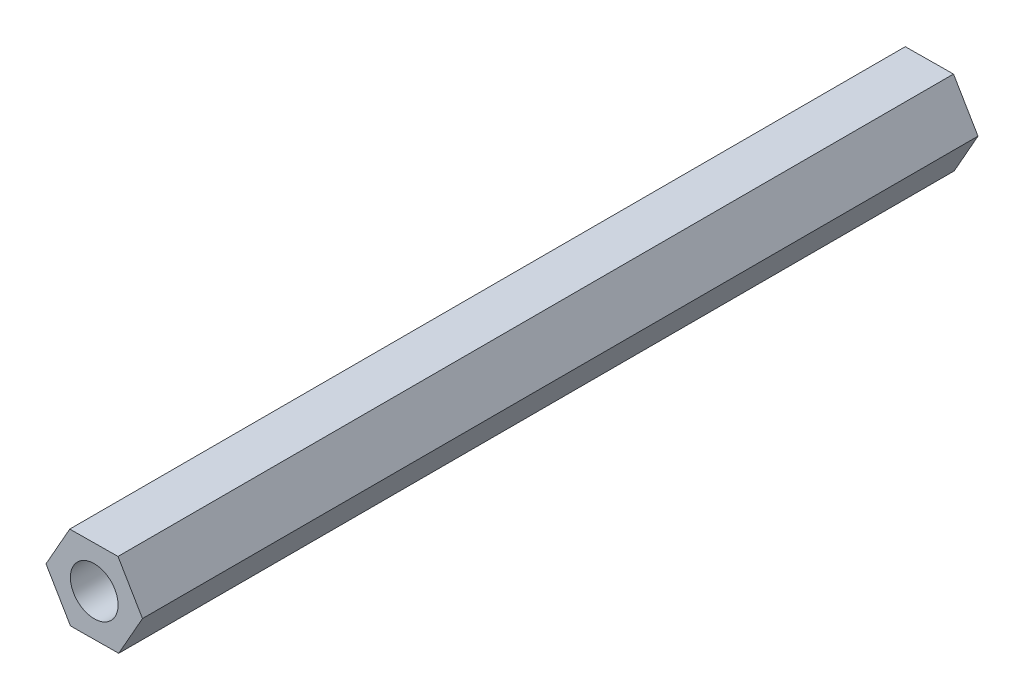
SolidWorks part; units mm, degrees
ref_plane "前视基准面" through (0, 0, 0) normal (0, 0, 1) x (1, 0, 0)
ref_plane "上视基准面" through (0, 0, 0) normal (0, 1, 0) x (1, 0, 0)
ref_plane "右视基准面" through (0, 0, 0) normal (1, 0, 0) x (0, 0, -1)
sketch "草图1" plane through (0, 0, 0) normal (0, 0, 1) x (1, 0, 0)
  line L1 (2.0515, -3.4821) -> (4.0413, 0.0356)
  line L2 (4.0413, 0.0356) -> (1.9898, 3.5177)
  line L3 (1.9898, 3.5177) -> (-2.0515, 3.4821)
  line L4 (-2.0515, 3.4821) -> (-4.0413, -0.0356)
  line L5 (-4.0413, -0.0356) -> (-1.9898, -3.5177)
  line L6 (-1.9898, -3.5177) -> (2.0515, -3.4821)
  circle A0 centre (0, 0) radius 3.5 construction
  circle A1 centre (0, 0) radius 2
extrude "凸台-拉伸1" add sketch "草图1" along normal blind 70
